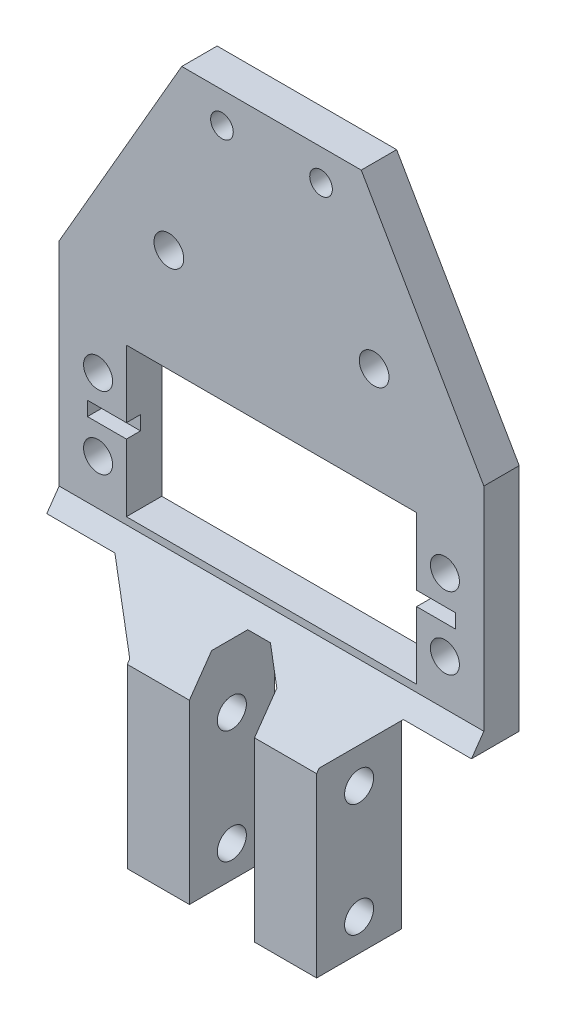
SolidWorks part; units mm, degrees
ref_plane "Front Plane" through (0, 0, 0) normal (1, 0, 0) x (0, 1, 0)
ref_plane "Top Plane" through (0, 0, 0) normal (0, 0, 1) x (0, 1, 0)
ref_plane "Right Plane" through (0, 0, 0) normal (0, 1, 0) x (-1, 0, 0)
sketch "Sketch2" plane through (0, 0, 0) normal (1, 0, 0) x (0, 1, 0)
  line L0 (0, 0) -> (0, 4.4753) construction
  line L1 (-12.5, 6) -> (12.5, 6)
  line L2 (-12.5, 6) -> (-12.5, -6)
  line L3 (-12.5, -6) -> (12.5, -6)
  line L5 (-12.5, 6) -> (12.5, -6) construction
  line L6 (-12.5, -6) -> (12.5, 6) construction
  line L7 (12.5, -6) -> (82.5, -6)
  line L8 (82.5, -6) -> (82.5, -1)
  line L9 (82.5, -1) -> (22.5, -1)
  line L10 (22.5, -1) -> (12.5, 6)
  circle A0 centre (-8, 0) radius 2.05
  circle A1 centre (8, 0) radius 2.05
  point P0 (0, 0)
  dimension "D3" = 4.1
  dimension "D1" = 25
  dimension "D2" = 12
  dimension "D4" = 16
  dimension "D5" = 70
  dimension "D6" = 5
  dimension "D7" = 60
  dimension "D8" = 12.2066
extrude "Boss-Extrude1" add sketch "Sketch2" along normal mid plane 60
sketch "Sketch3" plane through (0, 0, 0) normal (0, 1, 0) x (-1, 0, 0)
  line L0 (-30, 6) -> (-30, -6) construction
  line L1 (4.6, 7.5) -> (-4.6, 7.5)
  line L2 (4.6, 7.5) -> (4.6, -7.5)
  line L3 (4.6, -7.5) -> (-4.6, -7.5)
  line L4 (-4.6, 7.5) -> (-4.6, -7.5)
  line L5 (4.6, 7.5) -> (-4.6, -7.5) construction
  line L6 (4.6, -7.5) -> (-4.6, 7.5) construction
  line L7 (-13.375, 7.5) -> (-46.625, 7.5)
  line L8 (-13.375, 7.5) -> (-13.375, -7.5)
  line L9 (-13.375, -7.5) -> (-46.625, -7.5)
  line L10 (-46.625, 7.5) -> (-46.625, -7.5)
  line L11 (-13.375, 7.5) -> (-46.625, -7.5) construction
  line L12 (-13.375, -7.5) -> (-46.625, 7.5) construction
  line L13 (0, 0) -> (0, 2.9365) construction
  line L14 (13.375, -7.5) -> (46.625, 7.5) construction
  line L15 (13.375, 7.5) -> (46.625, -7.5) construction
  line L16 (46.625, 7.5) -> (46.625, -7.5)
  line L17 (13.375, -7.5) -> (46.625, -7.5)
  line L18 (13.375, 7.5) -> (13.375, -7.5)
  line L19 (13.375, 7.5) -> (46.625, 7.5)
  point P0 (0, 0)
  point P6 (-30, 0)
  point P19 (30, 0)
  dimension "D1" = 9.2
  dimension "D2" = 33.25
  dimension "D3" = 15
  dimension "D4" = 15
extrude "Cut-Extrude1" cut sketch "Sketch3" along normal blind 32.5 from surface at -12.5 starting at face at (0, -12.5, 0)
chamfer "Chamfer1" distance 3 angle 45 2 edges at (-4.6, 20, -2.625) (4.6, 20, -2.625)
chamfer "Chamfer2" distance 7 angle 45 2 edges at (13.375, 20, -2.625) (-13.375, 20, -2.625)
sketch "Sketch4" plane through (0, 0, 0) normal (0, 0, 1) x (0, 1, 0)
  line L0 (0, 0) -> (7.4338, 0) construction
  line L1 (22.5, -30) -> (22.5, 30) construction
  line L4 (28.9, 24.5) -> (39.1, 24.5) construction
  line L5 (23.5, 20.5) -> (44.5, 20.5)
  line L6 (23.5, 20.5) -> (23.5, -20.5)
  line L7 (23.5, -20.5) -> (44.5, -20.5)
  line L8 (44.5, 20.5) -> (44.5, -20.5)
  line L9 (23.5, 20.5) -> (44.5, -20.5) construction
  line L10 (23.5, -20.5) -> (44.5, 20.5) construction
  line L11 (34, 0) -> (37.7394, 0) construction
  line L12 (34, 0) -> (34, 5.8106) construction
  circle A0 centre (39.1, 24.5) radius 2.05
  circle A1 centre (28.9, 24.5) radius 2.05
  circle A2 centre (28.9, -24.5) radius 2.05
  circle A3 centre (39.1, -24.5) radius 2.05
  circle A4 centre (34, 10) radius 7 construction
  point P9 (34, 0)
  point P14 (34, 24.5)
  dimension "D5" = 4.1
  dimension "D6" = 4.1
  dimension "D8" = 14
  dimension "D1" = 21
  dimension "D2" = 41
  dimension "D3" = 1
  dimension "D4" = 10.2
  dimension "D7" = 49
  dimension "D9" = 14.5
extrude "Cut-Extrude2" cut sketch "Sketch4" against normal blind 30
sketch "Sketch5" plane through (0, 0, 0) normal (0, 0, 1) x (0, 1, 0)
  line L0 (0, 0) -> (34, 0) construction
  line L1 (28.9, 24.5) -> (39.1, 24.5) construction
  line L2 (34, 24.5) -> (34, -16.8217) construction
  circle A0 centre (59.1, 14.5) radius 2.1
  circle A1 centre (39.1, 24.5) radius 2.05 construction
  circle A2 centre (59.1, -14.5) radius 2.1
  circle A3 centre (59.1, 14.5) radius 15 construction
  circle A4 centre (59.1, -14.5) radius 15 construction
  circle A5 centre (34, 10) radius 11.5 construction
  circle A6 centre (78.1, 7) radius 1.6
  circle A7 centre (78.1, -7) radius 1.6
  dimension "D2" = 4.2
  dimension "D4" = 30
  dimension "D5" = 23
  dimension "D7" = 3.2
  dimension "D1" = 10
  dimension "D3" = 20
  dimension "D6" = 14.5
  dimension "D8" = 19
  dimension "D9" = 7.5
extrude "Cut-Extrude3" cut sketch "Sketch5" against normal blind 10
sketch "Sketch6" plane through (0, 0, 0) normal (0, 0, 1) x (0, 1, 0)
  line L0 (52.5, 30) -> (82.5, 12.6795)
  line L1 (82.5, 30) -> (22.5, 30) construction
  line L2 (82.5, -30) -> (82.5, 30) construction
  line L3 (82.5, 12.6795) -> (82.5, -12.6795)
  line L4 (52.5, 30) -> (52.5, 35)
  line L5 (52.5, 35) -> (87.5, 35)
  line L6 (87.5, 35) -> (87.5, -35)
  line L7 (-6.6, 0) -> (6.6, 0) construction
  line L8 (52.5, -35) -> (87.5, -35)
  line L9 (52.5, -30) -> (52.5, -35)
  line L10 (52.5, -30) -> (82.5, -12.6795)
  point P14 (87.5, 0)
  point P17 (82.5, 0)
  dimension "D1" = 35
  dimension "D2" = 30
  dimension "D3" = 5
extrude "Cut-Extrude4" cut sketch "Sketch6" against normal blind 10
sketch "Sketch8" plane through (0, 0, 0) normal (0, 0, 1) x (0, 1, 0)
  line L1 (33, 26) -> (35, 26)
  line L2 (33, 26) -> (33, -26)
  line L3 (33, -26) -> (35, -26)
  line L4 (35, 26) -> (35, -26)
  line L5 (33, 26) -> (35, -26) construction
  line L6 (33, -26) -> (35, 26) construction
  point P0 (34, 0)
  dimension "D1" = 34
  dimension "D2" = 52
  dimension "D3" = 2
extrude "Cut-Extrude6" cut sketch "Sketch8" against normal blind 2 from surface at -1 starting at face at (-14.5, 61.2, -1)
